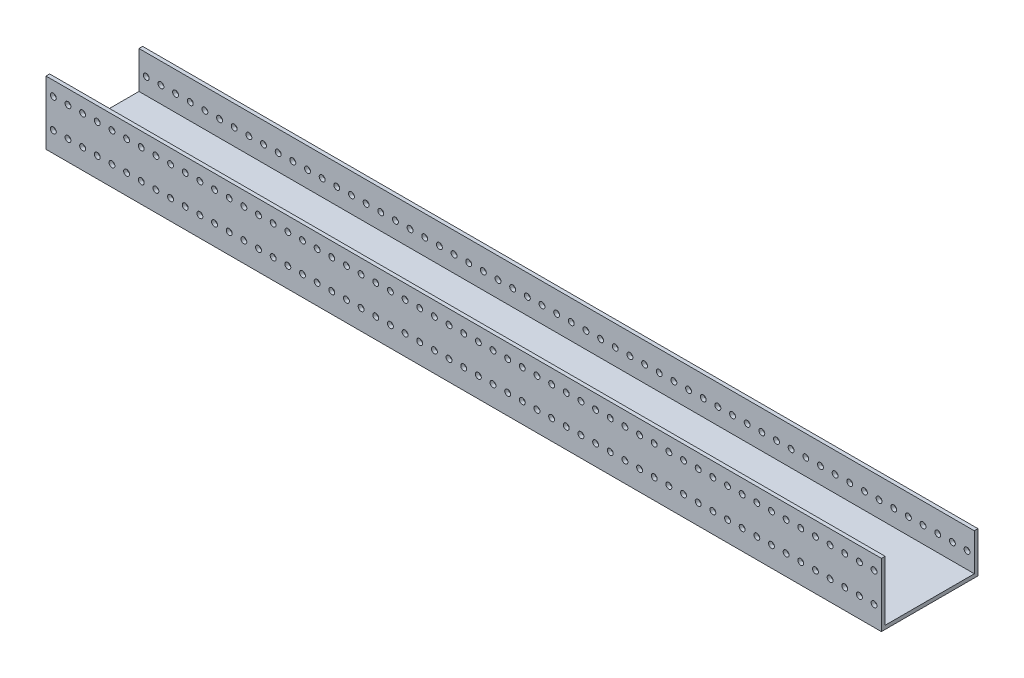
SolidWorks part; units mm, degrees
ref_plane "Front Plane" through (0, 0, 0) normal (0, 0, 1) x (1, 0, 0)
ref_plane "Top Plane" through (0, 0, 0) normal (0, 1, 0) x (1, 0, 0)
ref_plane "Right Plane" through (0, 0, 0) normal (1, 0, 0) x (0, 0, -1)
sketch "Sketch1" plane through (0, 0, 0) normal (0, 1, 0) x (1, 0, 0)
  line L1 (0, 0) -> (723.9, 0)
  line L2 (0, 0) -> (0, 83.7184)
  line L3 (0, 83.7184) -> (723.9, 83.7184)
  line L4 (723.9, 0) -> (723.9, 83.7184)
  dimension "D1" = 83.7184
  dimension "D2" = 723.9
extrude "Boss-Extrude1" add sketch "Sketch1" along normal blind 55.0164
sketch "Sketch3" plane through (723.9, 0, 0) normal (1, 0, 0) x (0, 0, -1)
  line L0 (0, 55.0164) -> (83.7184, 55.0164) construction
  line L1 (3.175, 55.0164) -> (80.5434, 55.0164)
  line L2 (3.175, 55.0164) -> (3.175, 3.175)
  line L3 (3.175, 3.175) -> (80.5434, 3.175)
  line L4 (80.5434, 55.0164) -> (80.5434, 3.175)
  line L6 (0, 55.0164) -> (0, 0) construction
  line L7 (0, 0) -> (83.7184, 0) construction
  line L8 (83.7184, 55.0164) -> (83.7184, 0) construction
  line L10 (80.5434, 55.0164) -> (83.7184, 55.0164)
  line L11 (80.5434, 55.0164) -> (80.5434, 35.433)
  line L12 (80.5434, 35.433) -> (83.7184, 35.433)
  line L13 (83.7184, 55.0164) -> (83.7184, 35.433)
  line M11 (83.7184, 55.0164) -> (0, 55.0164)
  dimension "D1" = 3.175
  dimension "D2" = 3.175
  dimension "D3" = 3.175
  dimension "D4" = 19.5834
extrude "Cut-Extrude1" cut sketch "Sketch3" against normal up to next contours L4 L2 L3 M11 | L10 L13 L12 L11
sketch "Sketch6" plane through (0, 0, 0) normal (0, 0, 1) x (1, 0, 0)
  line L0 (0, 55.0164) -> (0, 0) construction
  line L1 (0, 0) -> (723.9, 0) construction
  line L2 (0, 55.0164) -> (723.9, 55.0164) construction
  circle A0 centre (6.35, 42.8244) radius 2.5527
  circle A1 centre (19.05, 42.8244) radius 2.5527
  circle A2 centre (31.75, 42.8244) radius 2.5527
  circle A3 centre (44.45, 42.8244) radius 2.5527
  circle A4 centre (57.15, 42.8244) radius 2.5527
  circle A5 centre (69.85, 42.8244) radius 2.5527
  circle A6 centre (82.55, 42.8244) radius 2.5527
  circle A7 centre (95.25, 42.8244) radius 2.5527
  circle A8 centre (107.95, 42.8244) radius 2.5527
  circle A9 centre (120.65, 42.8244) radius 2.5527
  circle A10 centre (133.35, 42.8244) radius 2.5527
  circle A11 centre (146.05, 42.8244) radius 2.5527
  circle A12 centre (158.75, 42.8244) radius 2.5527
  circle A13 centre (171.45, 42.8244) radius 2.5527
  circle A14 centre (184.15, 42.8244) radius 2.5527
  circle A15 centre (196.85, 42.8244) radius 2.5527
  circle A16 centre (209.55, 42.8244) radius 2.5527
  circle A17 centre (222.25, 42.8244) radius 2.5527
  circle A18 centre (234.95, 42.8244) radius 2.5527
  circle A19 centre (247.65, 42.8244) radius 2.5527
  circle A20 centre (260.35, 42.8244) radius 2.5527
  circle A21 centre (273.05, 42.8244) radius 2.5527
  circle A22 centre (285.75, 42.8244) radius 2.5527
  circle A23 centre (298.45, 42.8244) radius 2.5527
  circle A24 centre (311.15, 42.8244) radius 2.5527
  circle A25 centre (323.85, 42.8244) radius 2.5527
  circle A26 centre (336.55, 42.8244) radius 2.5527
  circle A27 centre (349.25, 42.8244) radius 2.5527
  circle A28 centre (361.95, 42.8244) radius 2.5527
  circle A29 centre (374.65, 42.8244) radius 2.5527
  circle A30 centre (387.35, 42.8244) radius 2.5527
  circle A31 centre (400.05, 42.8244) radius 2.5527
  circle A32 centre (412.75, 42.8244) radius 2.5527
  circle A33 centre (425.45, 42.8244) radius 2.5527
  circle A34 centre (438.15, 42.8244) radius 2.5527
  circle A35 centre (450.85, 42.8244) radius 2.5527
  circle A36 centre (463.55, 42.8244) radius 2.5527
  circle A37 centre (476.25, 42.8244) radius 2.5527
  circle A38 centre (488.95, 42.8244) radius 2.5527
  circle A39 centre (501.65, 42.8244) radius 2.5527
  circle A40 centre (514.35, 42.8244) radius 2.5527
  circle A41 centre (527.05, 42.8244) radius 2.5527
  circle A42 centre (539.75, 42.8244) radius 2.5527
  circle A43 centre (552.45, 42.8244) radius 2.5527
  circle A44 centre (565.15, 42.8244) radius 2.5527
  circle A45 centre (577.85, 42.8244) radius 2.5527
  circle A46 centre (590.55, 42.8244) radius 2.5527
  circle A47 centre (603.25, 42.8244) radius 2.5527
  circle A48 centre (615.95, 42.8244) radius 2.5527
  circle A49 centre (628.65, 42.8244) radius 2.5527
  circle A50 centre (641.35, 42.8244) radius 2.5527
  circle A51 centre (654.05, 42.8244) radius 2.5527
  circle A52 centre (666.75, 42.8244) radius 2.5527
  circle A53 centre (679.45, 42.8244) radius 2.5527
  circle A54 centre (692.15, 42.8244) radius 2.5527
  circle A55 centre (704.85, 42.8244) radius 2.5527
  circle A56 centre (717.55, 42.8244) radius 2.5527
  circle A57 centre (19.05, 17.4244) radius 2.5527
  circle A58 centre (31.75, 17.4244) radius 2.5527
  circle A59 centre (44.45, 17.4244) radius 2.5527
  circle A60 centre (57.15, 17.4244) radius 2.5527
  circle A61 centre (69.85, 17.4244) radius 2.5527
  circle A62 centre (82.55, 17.4244) radius 2.5527
  circle A63 centre (95.25, 17.4244) radius 2.5527
  circle A64 centre (107.95, 17.4244) radius 2.5527
  circle A65 centre (120.65, 17.4244) radius 2.5527
  circle A66 centre (133.35, 17.4244) radius 2.5527
  circle A67 centre (146.05, 17.4244) radius 2.5527
  circle A68 centre (158.75, 17.4244) radius 2.5527
  circle A69 centre (171.45, 17.4244) radius 2.5527
  circle A70 centre (184.15, 17.4244) radius 2.5527
  circle A71 centre (196.85, 17.4244) radius 2.5527
  circle A72 centre (209.55, 17.4244) radius 2.5527
  circle A73 centre (222.25, 17.4244) radius 2.5527
  circle A74 centre (234.95, 17.4244) radius 2.5527
  circle A75 centre (247.65, 17.4244) radius 2.5527
  circle A76 centre (260.35, 17.4244) radius 2.5527
  circle A77 centre (273.05, 17.4244) radius 2.5527
  circle A78 centre (285.75, 17.4244) radius 2.5527
  circle A79 centre (298.45, 17.4244) radius 2.5527
  circle A80 centre (311.15, 17.4244) radius 2.5527
  circle A81 centre (323.85, 17.4244) radius 2.5527
  circle A82 centre (336.55, 17.4244) radius 2.5527
  circle A83 centre (349.25, 17.4244) radius 2.5527
  circle A84 centre (361.95, 17.4244) radius 2.5527
  circle A85 centre (374.65, 17.4244) radius 2.5527
  circle A86 centre (387.35, 17.4244) radius 2.5527
  circle A87 centre (400.05, 17.4244) radius 2.5527
  circle A88 centre (412.75, 17.4244) radius 2.5527
  circle A89 centre (425.45, 17.4244) radius 2.5527
  circle A90 centre (438.15, 17.4244) radius 2.5527
  circle A91 centre (450.85, 17.4244) radius 2.5527
  circle A92 centre (463.55, 17.4244) radius 2.5527
  circle A93 centre (476.25, 17.4244) radius 2.5527
  circle A94 centre (488.95, 17.4244) radius 2.5527
  circle A95 centre (501.65, 17.4244) radius 2.5527
  circle A96 centre (514.35, 17.4244) radius 2.5527
  circle A97 centre (527.05, 17.4244) radius 2.5527
  circle A98 centre (539.75, 17.4244) radius 2.5527
  circle A99 centre (552.45, 17.4244) radius 2.5527
  circle A100 centre (565.15, 17.4244) radius 2.5527
  circle A101 centre (577.85, 17.4244) radius 2.5527
  circle A102 centre (590.55, 17.4244) radius 2.5527
  circle A103 centre (603.25, 17.4244) radius 2.5527
  circle A104 centre (615.95, 17.4244) radius 2.5527
  circle A105 centre (628.65, 17.4244) radius 2.5527
  circle A106 centre (641.35, 17.4244) radius 2.5527
  circle A107 centre (654.05, 17.4244) radius 2.5527
  circle A108 centre (666.75, 17.4244) radius 2.5527
  circle A109 centre (679.45, 17.4244) radius 2.5527
  circle A110 centre (692.15, 17.4244) radius 2.5527
  circle A111 centre (704.85, 17.4244) radius 2.5527
  circle A112 centre (717.55, 17.4244) radius 2.5527
  circle A113 centre (6.35, 17.4244) radius 2.5527
  dimension "D3" = 5.1054
  dimension "D1" = 6.35
  dimension "D2" = 12.192
  dimension "D6" = 17.4244
  dimension "D4" = 57
  dimension "D5" = 2
extrude "Cut-Extrude2" cut sketch "Sketch6" against normal up to next (3.175 mm away)
sketch "Sketch7" plane through (0, 0, -83.7184) normal (0, 0, -1) x (-1, 0, 0)
  line L0 (-723.9, 35.433) -> (-723.9, 0) construction
  line L1 (-723.9, 0) -> (0, 0) construction
  circle A0 centre (-717.55, 17.4244) radius 2.5527
  dimension "D1" = 5.1054
  dimension "D2" = 6.35
  dimension "D3" = 17.4244
extrude "Cut-Extrude3" cut sketch "Sketch7" against normal up to next
pattern_linear "LPattern1" count 57 spacing 12.7 along (-1, 0, 0) of "Cut-Extrude3"
